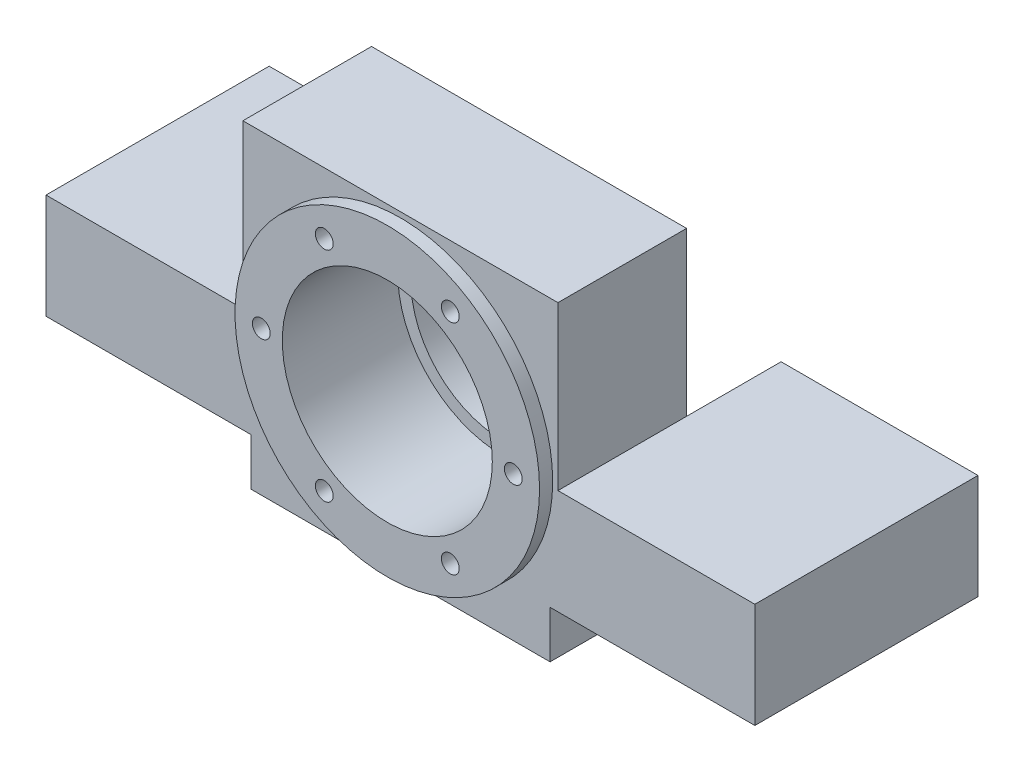
SolidWorks part; units mm, degrees
ref_plane "前视基准面" through (0, 0, 0) normal (0, 0, 1) x (1, 0, 0)
ref_plane "上视基准面" through (0, 0, 0) normal (0, 1, 0) x (1, 0, 0)
ref_plane "右视基准面" through (0, 0, 0) normal (1, 0, 0) x (0, 0, -1)
other "Configuration Table"
sketch "草图1" plane through (0, 0, 0) normal (0, 0, 1) x (1, 0, 0)
  line L0 (57, 0) -> (-57, 0) construction
  line L1 (0, 0) -> (-57, 0)
  line L3 (-135, 58) -> (-135, 18)
  line L5 (135, 58) -> (135, 18)
  line L6 (-57, 0) -> (-57, 18)
  line L7 (-57, 18) -> (-135, 18)
  line L8 (0, 0) -> (57, 0)
  line L9 (57, 0) -> (57, 18)
  line L10 (57, 18) -> (135, 18)
  line L11 (-135, 58) -> (-60, 58)
  line L12 (-60, 58) -> (-60, 120)
  line L13 (-60, 120) -> (60, 120)
  line L14 (60, 120) -> (60, 58)
  line L15 (60, 58) -> (135, 58)
  dimension "D1" = 75
  dimension "D2" = 120
  dimension "D3" = 57
  dimension "D4" = 18
  dimension "D5" = 57
  dimension "D6" = 18
  dimension "D7" = 40
  dimension "D8" = 120
extrude "凸台-拉伸1" add sketch "草图1" against normal blind 85
sketch "草图2" plane through (0, 0, 0) normal (0, 0, 1) x (1, 0, 0)
  line L0 (0, 0) -> (0, 60) construction
  circle A0 centre (0, 60) radius 58
  dimension "D1" = 116
extrude "凸台-拉伸2" add sketch "草图2" along normal blind 5
sketch "草图3" plane through (0, 0, 5) normal (0, 0, 1) x (1, 0, 0)
  circle A0 centre (0, 60) radius 40
extrude "切除-拉伸1" cut sketch "草图3" against normal blind 44
sketch "草图4" plane through (0, 0, -39) normal (0, 0, 1) x (1, 0, 0)
  circle A0 centre (0, 60) radius 35
extrude "切除-拉伸2" cut sketch "草图4" against normal through all
sketch "草图5" plane through (0, 0, 5) normal (0, 0, 1) x (1, 0, 0)
  circle A0 centre (0, 60) radius 48 construction
  point P13 (24, 101.5692)
  dimension "D2" = 96
hole_wizard "M8 螺纹孔1" positions "草图6" profile "草图7" tap size "M8" standard "GB"
sketch "草图6" plane through (0, 0, 5) normal (0, 0, 1) x (1, 0, 0)
  point P0 (24, 101.5692)
sketch "草图7" plane through (24, 101.5692, 5) normal (1, 0, 0) x (0, -1, 0)
  line L0 (0, 0) -> (0, 29.8029)
  line L1 (0, 29.8029) -> (3.4, 27.76)
  line L2 (3.4, 27.76) -> (3.4, 0)
  line L5 (3.4, 0) -> (0, 0)
  line L10 (0, 29.8029) -> (-3.4, 27.76) construction
  line L11 (0, -6.35) -> (0, 107.95) construction
  dimension "螺纹孔钻头直径" = 6.8
  dimension "螺纹孔钻头深度" = 27.76
  dimension "导头角度" = 118
cosmetic thread "孔螺纹线1" parameters "D1"=21, "D2"=8
pattern_circular "阵列(圆周)1" count 6 over 360 about axis through (0, 60, 0) along (0, 0, 1) of "M8 螺纹孔1"
sketch "草图8" plane through (0, 120, 0) normal (0, 1, 0) x (1, 0, 0)
  line L0 (60, 85) -> (60, 0) construction
  line L1 (-60, 85) -> (60, 85)
  line L2 (-60, 85) -> (-60, 49)
  line L3 (-60, 49) -> (60, 49)
  line L4 (60, 85) -> (60, 49)
  dimension "D1" = 36
extrude "切除-拉伸3" cut sketch "草图8" against normal through all
